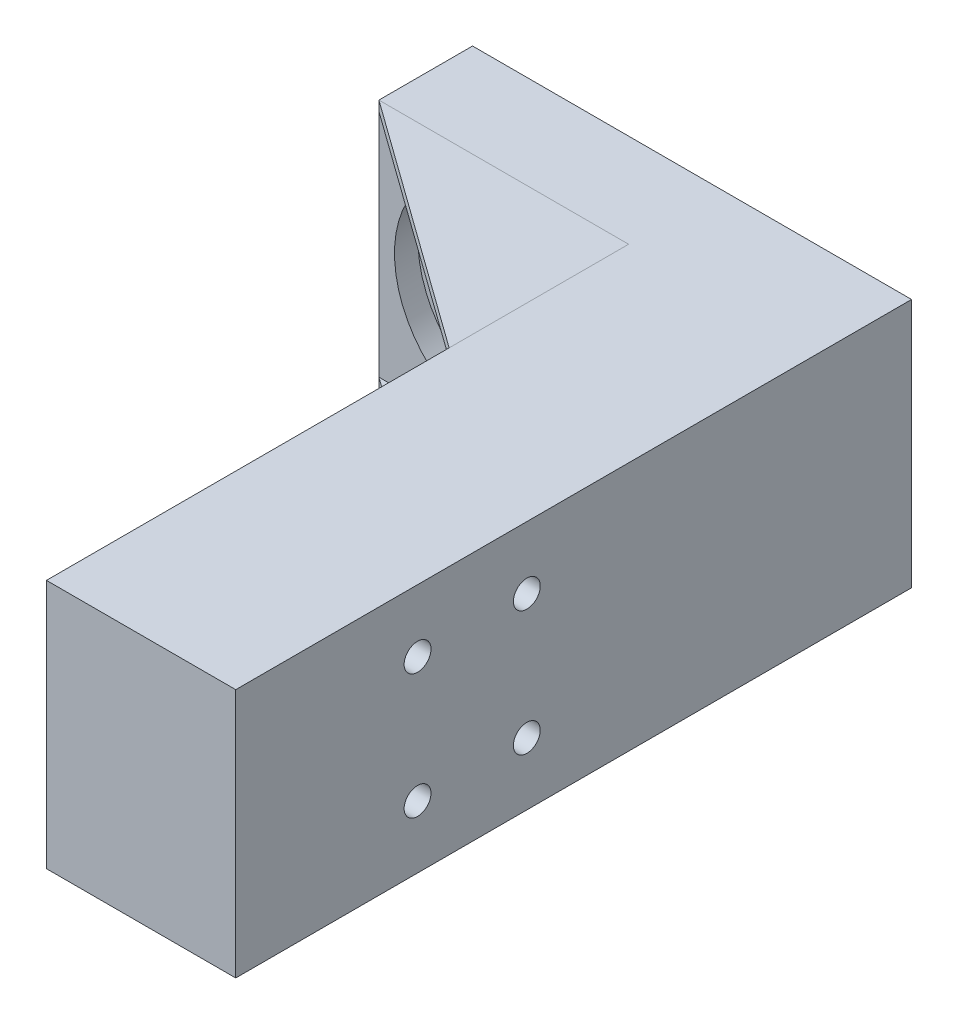
SolidWorks part; units mm, degrees
material "ABS"
ref_plane "Front Plane" through (0, 0, 0) normal (1, 0, 0) x (0, 1, 0)
ref_plane "Top Plane" through (0, 0, 0) normal (0, 0, 1) x (0, 1, 0)
ref_plane "Right Plane" through (0, 0, 0) normal (0, 1, 0) x (-1, 0, 0)
sketch "Sketch1" plane through (0, 0, 0) normal (0, 0, 1) x (0, 1, 0)
  line L1 (0, 0) -> (32, 0)
  line L2 (0, 0) -> (0, 32)
  line L3 (0, 32) -> (32, 32)
  line L4 (32, 0) -> (32, 32)
  dimension "D1" = 32
  dimension "D2" = 32
extrude "Boss-Extrude1" add sketch "Sketch1" along normal blind 12
sketch "Sketch2" plane through (0, 0, 0) normal (1, 0, 0) x (0, 1, 0)
  line L1 (0, 0) -> (32, 0)
  line L2 (0, 0) -> (0, 86.6)
  line L3 (0, 86.6) -> (32, 86.6)
  line L4 (32, 0) -> (32, 86.6)
  dimension "D1" = 32
  dimension "D2" = 86.6
extrude "Boss-Extrude2" add sketch "Sketch2" along normal blind 24.2564
sketch "Sketch3" plane through (0, 0, 12) normal (0, 0, 1) x (1, 0, 0)
  line L1 (-16, 32) -> (-16, 0) construction
  line L3 (0, 32) -> (-32, 32) construction
  line L4 (6.6, 0) -> (-6.6, 0) construction
  line L5 (-32, 16) -> (24.2564, 16) construction
  line L6 (-32, 32) -> (-32, 0) construction
  line L7 (24.2564, 32) -> (24.2564, 0) construction
  circle A0 centre (-16, 16) radius 14
  point P0 (-16, 32)
  dimension "D1" = 28
extrude "Cut-Extrude1" cut sketch "Sketch3" against normal blind 3
sketch "Sketch4" plane through (0, 0, 9) normal (0, 0, 1) x (1, 0, 0)
  circle A0 centre (-15.9578, 16.1108) radius 3
  dimension "D1" = 6
extrude "Cut-Extrude2" cut sketch "Sketch4" against normal through all
sketch "Sketch9" plane through (0, 0, 9) normal (0, 0, 1) x (1, 0, 0)
  circle A1 centre (-16, 25.35) radius 1.72
  circle A3 centre (-16, 6.65) radius 1.72
  circle A4 centre (-6.65, 16) radius 1.72
  circle A5 centre (-25.3078, 16) radius 1.72
  dimension "D1" = 3.44
  dimension "D2" = 9.35
  dimension "D3" = 3.44
  dimension "D5" = 3.44
  dimension "D7" = 3.44
  dimension "D4" = 9.35
  dimension "D6" = 9.35
  dimension "D8" = 9.35
extrude "Cut-Extrude3" cut sketch "Sketch9" against normal through all
sketch "Sketch10" plane through (0, 0, 0) normal (-1, 0, 0) x (0, -1, 0)
  line L0 (-16, 86.6) -> (-16, 12) construction
  line L1 (-32, 86.6) -> (0, 86.6) construction
  line L2 (-32, 12) -> (0, 12) construction
  line L3 (-32, 49.3) -> (0, 49.3) construction
  line L4 (-32, 12) -> (-32, 86.6) construction
  line L5 (0, 30.941) -> (0, -30.941) construction
  line L6 (-32, 63.3) -> (0, 63.3) construction
  circle A0 centre (-24, 63.3) radius 1.72
  circle A1 centre (-24, 49.3) radius 1.72
  circle A2 centre (-8, 63.3) radius 1.72
  circle A3 centre (-8, 49.3) radius 1.72
  dimension "D1" = 3.44
  dimension "D4" = 3.44
  dimension "D6" = 3.44
  dimension "D8" = 3.44
  dimension "D2" = 14
  dimension "D3" = 8
  dimension "D5" = 8
  dimension "D7" = 8
  dimension "D9" = 8
extrude "Cut-Extrude4" cut sketch "Sketch10" against normal through all
sketch "Sketch12" plane through (0, 0, 0) normal (0, 1, 0) x (-1, 0, 0)
  line L0 (0, 35) -> (34.7666, 35) construction
  line L1 (0, 86.6) -> (0, 12) construction
  line L2 (32, 12) -> (0, 12)
  line L3 (0, 12) -> (0, 35)
  line L4 (0, 35) -> (32, 12)
  dimension "D1" = 35
extrude "Boss-Extrude4" add sketch "Sketch12" along normal blind 1.25
sketch3d "3DSketch5"
  line L2 (0, 0, 35) -> (0, 32, 35) construction
  line L3 (0, 32, 12) -> (0, 32, 86.6) construction
  line L4 (0, 32, 35) -> (0, 32, 12)
  line L5 (0, 32, 12) -> (-32, 32, 12)
  line L6 (-32, 32, 12) -> (0, 32, 35)
  line L7 (-32, 1.25, 12) -> (0, 1.25, 35) construction
  dimension "D1" = 30.75
extrude "Boss-Extrude5" add sketch "3DSketch5" along direction (0, 1, 0) on the side of the normal blind 1.25 separate body contours L4 L5 L6
equation "\"P\"= 300'Load in N"
equation "\"SF\"= 3'safety Factor"
equation "\"DM\"= 0.3mm'Deflection Max"
equation "\"SY\"= 30'Yield Strength in MPa"
equation "\"E\"= 2000'Young Modulus In MPa"
equation "\"B\"= 32mm'Base"
equation "\"Mom1\"= \"P\" * 18'Moment of Feature 1"
equation "\"MOI\"= \"Mom1\" * ( \"B\" ^ 2 ) / ( 2 * \"E\" * \"DM\" )'mm^4 (Moment of Inertia 1)"
equation "\"t1\"= ( ( \"MOI\" * 12 ) / ( 32 ) ) ^ ( 1 / 3 )'\"height\" of feat. 1"
equation "\"Lengthofmotor\"= 74.6mm"
equation "\"LengthT\"= \"Lengthofmotor\" + 12'total length of part"
equation "\"Mom2\"= \"P\" * ( \"LengthT\" + 18 )'Moment feat. 2"
equation "\"t2.1\"= ( ( 6 * \"Mom2\" * \"LengthT\" ) / ( \"E\" * \"DM\" * \"B\" ) ) ^ ( 1 / 3 )"
equation "\"t2\"= ( ( 6 * \"Mom2\" * \"SF\" ) / ( \"B\" * \"SY\" ) ) ^ ( 1 / 2 )'\"height\" of feat. 2"
equation "\"D1@Sketch1\"=\"B\""
equation "\"D2@Sketch1\"=\"B\""
equation "\"D1@Boss-Extrude1\"=\"t1\""
equation "\"D1@Sketch2\"=\"B\""
equation "\"D2@Sketch2\"=\"LengthT\""
equation "\"D1@Boss-Extrude2\"=\"t2\""
equation "\"GBsize\"= 28mm'Gearbox diameter"
equation "\"ShaftDia\"= 6mm'Shaft diameter"
equation "\"D1@Sketch3\"=\"GBsize\""
equation "\"D1@Sketch4\"=\"ShaftDia\""
